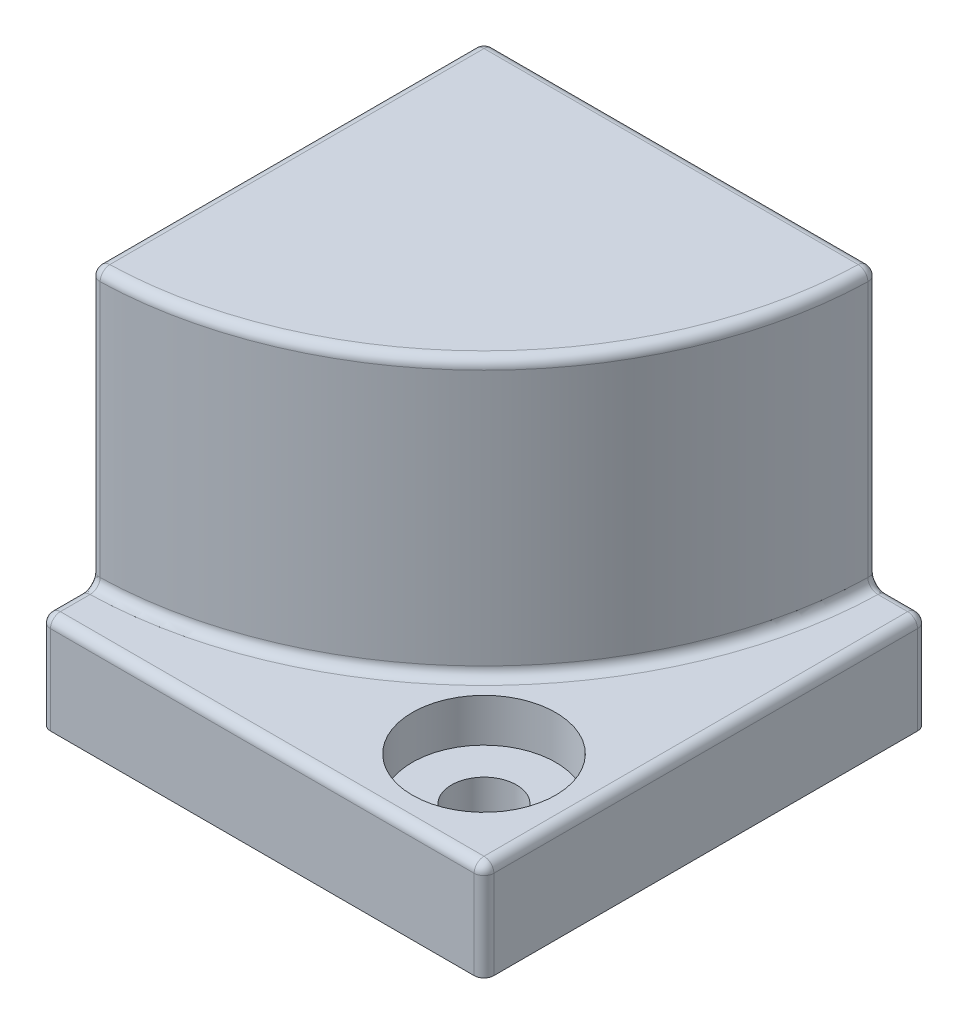
SolidWorks part; units mm, degrees
other "Markup1"
sketch "Sketch1" plane through (0, 0, 0) normal (0.5774, 0.5773, 0.5774) x (0.7071, 0, -0.7071)
sketch "Sketch2" plane through (0, 0, 0) normal (0.5774, 0.5773, 0.5774) x (0.7071, 0, -0.7071)
ref_plane "Front (z)" through (0, 0, 0) normal (0, 0, 1) x (1, 0, 0)
ref_plane "Top (y)" through (0, 0, 0) normal (0, 1, 0) x (1, 0, 0)
ref_plane "Right (x)" through (0, 0, 0) normal (1, 0, 0) x (0, 0, -1)
sketch "Sketch3" plane through (0, 0, 0) normal (0, 1, 0) x (1, 0, 0)
  line L1 (-22.5, -22.5) -> (22.5, -22.5)
  line L2 (-22.5, -22.5) -> (-22.5, 22.5)
  line L3 (-22.5, 22.5) -> (22.5, 22.5)
  line L4 (22.5, -22.5) -> (22.5, 22.5)
  line L5 (-22.5, -22.5) -> (22.5, 22.5) construction
  line L6 (-22.5, 22.5) -> (22.5, -22.5) construction
  point P0 (0, 0)
  dimension "D1" = 45
  dimension "D2" = 45
extrude "Boss-Extrude1" add sketch "Sketch3" along normal blind 10
hole_wizard "CBORE for M6 Hex Head Bolt1" positions "Sketch4" profile "Sketch5" counterbore size "M6" standard "ANSI Metric" end condition through all
sketch "Sketch4" plane through (0, 10, 0) normal (0, 1, 0) x (1, 0, 0)
  line L0 (-22.5, -22.5) -> (22.5, -22.5) construction
  line L1 (22.5, -22.5) -> (22.5, 22.5) construction
  point P0 (12.5, -12.5)
  dimension "D1" = 10
  dimension "D2" = 10
sketch "Sketch5" plane through (12.5, 10, 12.5) normal (1, 0, 0) x (0, 0, 1)
  line L0 (0, 0) -> (0, 10)
  line L1 (0, 10) -> (3.3, 10)
  line L3 (3.3, 10) -> (3.3, 4.38)
  line L4 (3.3, 4.38) -> (7.275, 4.38)
  line L5 (7.275, 4.38) -> (7.275, 0)
  line L7 (7.275, 0) -> (0, 0)
  line L11 (0, -6.35) -> (0, 107.95) construction
  dimension "Thru Hole Dia." = 6.6
  dimension "Thru Hole Depth" = 10
  dimension "C'Bore Dia." = 14.55
  dimension "C'Bore Depth" = 4.38
sketch "Sketch8" plane through (0, 10, 0) normal (0, 1, 0) x (1, 0, 0)
  line L0 (17.5, 22.5) -> (7.5, 22.5)
  line L1 (-22.5, -7.5) -> (-22.5, -17.5)
  arc A0 (-22.5, -7.5) -> (7.5, 22.5) centre (-22.5, 22.5) ccw
  arc A1 (-22.5, -17.5) -> (17.5, 22.5) centre (-22.5, 22.5) ccw
  circle A3 centre (-22.5, 22.5) radius 40 construction
  circle A4 centre (-22.5, 22.5) radius 30 construction
  point P4 (3.6891, 33.7712)
  point P9 (-5, 25)
  dimension "D1" = 60
  dimension "D2" = 10
extrude "Boss-Extrude3" add sketch "Sketch8" along normal blind 18
sketch "Sketch9" plane through (0, 28, 0) normal (0, 1, 0) x (1, 0, 0)
  line L0 (17.5, 22.5) -> (-22.5, 22.5)
  line L1 (-22.5, 22.5) -> (-22.5, -17.5)
  arc A0 (-22.5, -17.5) -> (17.5, 22.5) centre (-22.5, 22.5) ccw construction
  arc A1 (-22.5, -17.5) -> (17.5, 22.5) centre (-22.5, 22.5) ccw
extrude "Boss-Extrude4" add sketch "Sketch9" along normal blind 10
sketch "Sketch10" plane through (0, 10, 0) normal (0, 1, 0) x (1, 0, 0)
  line L0 (7.5, 22.5) -> (-22.5, 22.5) construction
  line L1 (-22.5, 22.5) -> (-22.5, -7.5) construction
  circle A0 centre (-10, 10) radius 3
  dimension "D1" = 6
  dimension "D2" = 12.5
  dimension "D3" = 12.5
extrude "Cut-Extrude2" cut sketch "Sketch10" against normal blind 6
fillet "Fillet2" radius 1 23 edges at (-22.5, 19, 7.5) (7.5, 19, -22.5) (-22.5, 28, -7.5) (-1.2868, 28, -1.2868) (-7.5, 28, -22.5) (-22.5, 10, -7.5) (-7.5, 10, -22.5) (-1.2868, 10, -1.2868) (-2.5, 38, -22.5) (5.7843, 38, 5.7843) (-22.5, 38, -2.5) (5.7843, 10, 5.7843) (-22.5, 10, 20) (0, 10, 22.5) (-22.5, 24, 17.5) (22.5, 10, 0) (20, 10, -22.5) (17.5, 24, -22.5) (-22.5, 5, 22.5) (-22.5, 5, -22.5) (22.5, 5, -22.5) (22.5, 5, 22.5) (-22.5, 33, -22.5)
